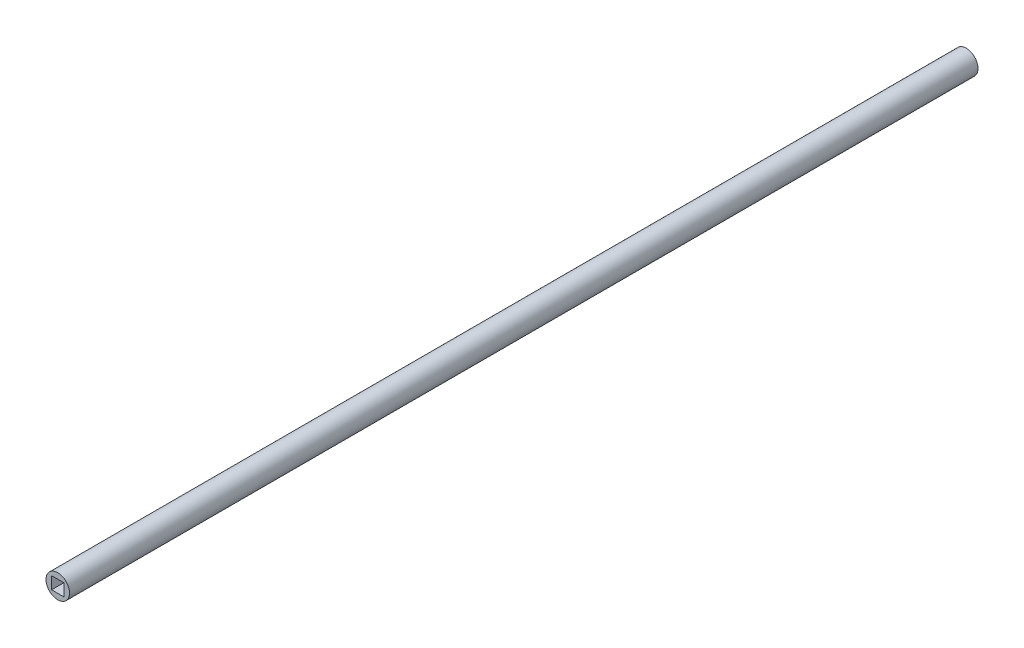
SolidWorks part; units mm, degrees
ref_plane "Front Plane" through (0, 0, 0) normal (0, 0, 1) x (1, 0, 0)
ref_plane "Top Plane" through (0, 0, 0) normal (0, 1, 0) x (1, 0, 0)
ref_plane "Right Plane" through (0, 0, 0) normal (1, 0, 0) x (0, 0, -1)
sketch "Sketch1" plane through (0, 0, 0) normal (0, 0, 1) x (1, 0, 0)
  line L1 (-1.651, 1.651) -> (1.651, 1.651)
  line L2 (-1.651, 1.651) -> (-1.651, -1.651)
  line L3 (-1.651, -1.651) -> (1.651, -1.651)
  line L4 (1.651, 1.651) -> (1.651, -1.651)
  line L5 (-1.651, 1.651) -> (1.651, -1.651) construction
  line L6 (-1.651, -1.651) -> (1.651, 1.651) construction
  circle A0 centre (0, 0) radius 3.175
  dimension "D1" = 6.35
  dimension "D2" = 4.6698
extrude "Boss-Extrude1" add sketch "Sketch1" along normal blind 245.36
